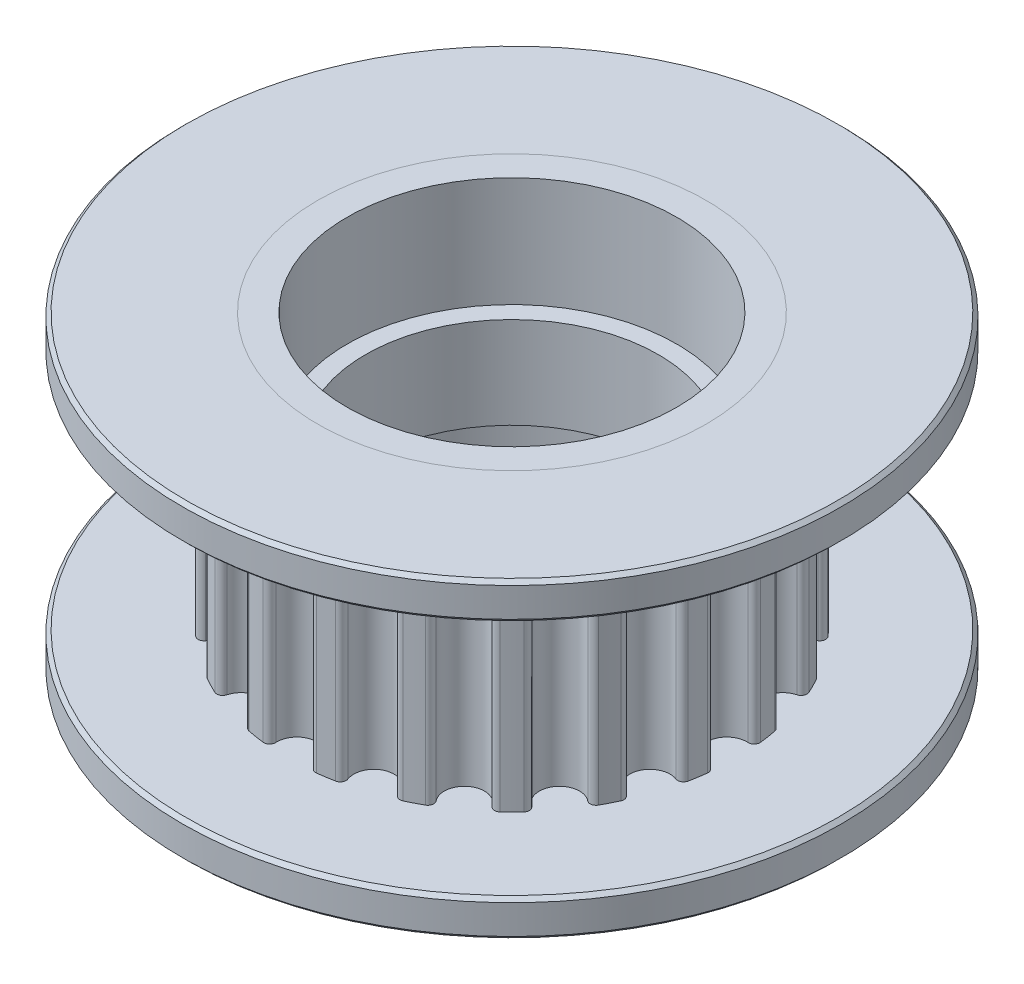
SolidWorks part; units mm, degrees
ref_plane "Přední rovina" through (0, 0, 0) normal (0, 0, 1) x (1, 0, 0)
ref_plane "Horní rovina" through (0, 0, 0) normal (0, 1, 0) x (1, 0, 0)
ref_plane "Pravá rovina" through (0, 0, 0) normal (1, 0, 0) x (0, 0, -1)
sketch "Skica1" plane through (0, 0, 0) normal (0, 0, 1) x (1, 0, 0)
  line L0 (0, 0) -> (0, 8.5) construction
  line L1 (4.5, 8.5) -> (5.3, 8.5)
  line L2 (5.3, 8.5) -> (5.3, 7.5)
  line L3 (5.3, 7.5) -> (9, 7.5)
  line L4 (9, 7.5) -> (9, 1)
  line L5 (4.5, 0) -> (5.3, 0)
  line L6 (5.3, 0) -> (5.3, 1)
  line L7 (5.3, 1) -> (9, 1)
  line L8 (4.5, 3) -> (4, 3)
  line L9 (4.5, 3) -> (4.5, 0)
  line L10 (4.5, 8.5) -> (4.5, 5.5)
  line L11 (4.5, 5.5) -> (4, 5.5)
  line L12 (4, 5.5) -> (4, 3)
  dimension "D1" = 6.5
  dimension "D2" = 2.5
  dimension "D3" = 3
  dimension "D4" = 9
  dimension "D5" = 4.5
  dimension "D6" = 5.3
  dimension "D7" = 8.5
revolve "Rotovat1" add sketch "Skica1" angle 360 about L0
sketch "Skica2" plane through (0, 7.5, 0) normal (0, 1, 0) x (1, 0, 0)
  arc A0 (-0.5492, 5.8991) -> (0.5492, 5.8991) centre (0, 5.87) ccw
  arc A1 (-0.5492, 5.8991) -> (-0.7281, 6.0665) centre (-0.709, 5.9076) ccw
  arc A2 (0.7281, 6.0665) -> (0.5492, 5.8991) centre (0.709, 5.9076) ccw
  arc A3 (1.1822, 5.9945) -> (0.7281, 6.0665) centre (0, 0) ccw
  arc A4 (1.3006, 5.7801) -> (2.3453, 5.4407) centre (1.8139, 5.5827) ccw
  arc A5 (1.3006, 5.7801) -> (1.1822, 5.9945) centre (1.1512, 5.8376) ccw
  arc A6 (2.5671, 5.5446) -> (2.3453, 5.4407) centre (2.4999, 5.3994) ccw
  arc A7 (2.9768, 5.3358) -> (2.5671, 5.5446) centre (0, 0) ccw
  arc A8 (3.0231, 5.0953) -> (3.9118, 4.4497) centre (3.4503, 4.7489) ccw
  arc A9 (3.0231, 5.0953) -> (2.9768, 5.3358) centre (2.8988, 5.1961) ccw
  arc A10 (4.1548, 4.4799) -> (3.9118, 4.4497) centre (4.046, 4.3626) ccw
  arc A11 (4.4799, 4.1548) -> (4.1548, 4.4799) centre (0, 0) ccw
  arc A12 (4.4497, 3.9118) -> (5.0953, 3.0231) centre (4.7489, 3.4503) ccw
  arc A13 (4.4497, 3.9118) -> (4.4799, 4.1548) centre (4.3626, 4.046) ccw
  arc A14 (5.3358, 2.9768) -> (5.0953, 3.0231) centre (5.1961, 2.8988) ccw
  arc A15 (5.5446, 2.5671) -> (5.3358, 2.9768) centre (0, 0) ccw
  arc A16 (5.4407, 2.3453) -> (5.7801, 1.3006) centre (5.5827, 1.8139) ccw
  arc A17 (5.4407, 2.3453) -> (5.5446, 2.5671) centre (5.3994, 2.4999) ccw
  arc A18 (5.9945, 1.1822) -> (5.7801, 1.3006) centre (5.8376, 1.1512) ccw
  arc A19 (6.0665, 0.7281) -> (5.9945, 1.1822) centre (0, 0) ccw
  arc A20 (5.8991, 0.5492) -> (5.8991, -0.5492) centre (5.87, 0) ccw
  arc A21 (5.8991, 0.5492) -> (6.0665, 0.7281) centre (5.9076, 0.709) ccw
  arc A22 (6.0665, -0.7281) -> (5.8991, -0.5492) centre (5.9076, -0.709) ccw
  arc A23 (5.9945, -1.1822) -> (6.0665, -0.7281) centre (0, 0) ccw
  arc A24 (5.7801, -1.3006) -> (5.4407, -2.3453) centre (5.5827, -1.8139) ccw
  arc A25 (5.7801, -1.3006) -> (5.9945, -1.1822) centre (5.8376, -1.1512) ccw
  arc A26 (5.5446, -2.5671) -> (5.4407, -2.3453) centre (5.3994, -2.4999) ccw
  arc A27 (5.3358, -2.9768) -> (5.5446, -2.5671) centre (0, 0) ccw
  arc A28 (5.0953, -3.0231) -> (4.4497, -3.9118) centre (4.7489, -3.4503) ccw
  arc A29 (5.0953, -3.0231) -> (5.3358, -2.9768) centre (5.1961, -2.8988) ccw
  arc A30 (4.4799, -4.1548) -> (4.4497, -3.9118) centre (4.3626, -4.046) ccw
  arc A31 (4.1548, -4.4799) -> (4.4799, -4.1548) centre (0, 0) ccw
  arc A32 (3.9118, -4.4497) -> (3.0231, -5.0953) centre (3.4503, -4.7489) ccw
  arc A33 (3.9118, -4.4497) -> (4.1548, -4.4799) centre (4.046, -4.3626) ccw
  arc A34 (2.9768, -5.3358) -> (3.0231, -5.0953) centre (2.8988, -5.1961) ccw
  arc A35 (2.5671, -5.5446) -> (2.9768, -5.3358) centre (0, 0) ccw
  arc A36 (2.3453, -5.4407) -> (1.3006, -5.7801) centre (1.8139, -5.5827) ccw
  arc A37 (2.3453, -5.4407) -> (2.5671, -5.5446) centre (2.4999, -5.3994) ccw
  arc A38 (1.1822, -5.9945) -> (1.3006, -5.7801) centre (1.1512, -5.8376) ccw
  arc A39 (0.7281, -6.0665) -> (1.1822, -5.9945) centre (0, 0) ccw
  arc A40 (0.5492, -5.8991) -> (-0.5492, -5.8991) centre (0, -5.87) ccw
  arc A41 (0.5492, -5.8991) -> (0.7281, -6.0665) centre (0.709, -5.9076) ccw
  arc A42 (-0.7281, -6.0665) -> (-0.5492, -5.8991) centre (-0.709, -5.9076) ccw
  arc A43 (-1.1822, -5.9945) -> (-0.7281, -6.0665) centre (0, 0) ccw
  arc A44 (-1.3006, -5.7801) -> (-2.3453, -5.4407) centre (-1.8139, -5.5827) ccw
  arc A45 (-1.3006, -5.7801) -> (-1.1822, -5.9945) centre (-1.1512, -5.8376) ccw
  arc A46 (-2.5671, -5.5446) -> (-2.3453, -5.4407) centre (-2.4999, -5.3994) ccw
  arc A47 (-2.9768, -5.3358) -> (-2.5671, -5.5446) centre (0, 0) ccw
  arc A48 (-3.0231, -5.0953) -> (-3.9118, -4.4497) centre (-3.4503, -4.7489) ccw
  arc A49 (-3.0231, -5.0953) -> (-2.9768, -5.3358) centre (-2.8988, -5.1961) ccw
  arc A50 (-4.1548, -4.4799) -> (-3.9118, -4.4497) centre (-4.046, -4.3626) ccw
  arc A51 (-4.4799, -4.1548) -> (-4.1548, -4.4799) centre (0, 0) ccw
  arc A52 (-4.4497, -3.9118) -> (-5.0953, -3.0231) centre (-4.7489, -3.4503) ccw
  arc A53 (-4.4497, -3.9118) -> (-4.4799, -4.1548) centre (-4.3626, -4.046) ccw
  arc A54 (-5.3358, -2.9768) -> (-5.0953, -3.0231) centre (-5.1961, -2.8988) ccw
  arc A55 (-5.5446, -2.5671) -> (-5.3358, -2.9768) centre (0, 0) ccw
  arc A56 (-5.4407, -2.3453) -> (-5.7801, -1.3006) centre (-5.5827, -1.8139) ccw
  arc A57 (-5.4407, -2.3453) -> (-5.5446, -2.5671) centre (-5.3994, -2.4999) ccw
  arc A58 (-5.9945, -1.1822) -> (-5.7801, -1.3006) centre (-5.8376, -1.1512) ccw
  arc A59 (-6.0665, -0.7281) -> (-5.9945, -1.1822) centre (0, 0) ccw
  arc A60 (-5.8991, -0.5492) -> (-5.8991, 0.5492) centre (-5.87, 0) ccw
  arc A61 (-5.8991, -0.5492) -> (-6.0665, -0.7281) centre (-5.9076, -0.709) ccw
  arc A62 (-6.0665, 0.7281) -> (-5.8991, 0.5492) centre (-5.9076, 0.709) ccw
  arc A63 (-5.9945, 1.1822) -> (-6.0665, 0.7281) centre (0, 0) ccw
  arc A64 (-5.7801, 1.3006) -> (-5.4407, 2.3453) centre (-5.5827, 1.8139) ccw
  arc A65 (-5.7801, 1.3006) -> (-5.9945, 1.1822) centre (-5.8376, 1.1512) ccw
  arc A66 (-5.5446, 2.5671) -> (-5.4407, 2.3453) centre (-5.3994, 2.4999) ccw
  arc A67 (-5.3358, 2.9768) -> (-5.5446, 2.5671) centre (0, 0) ccw
  arc A68 (-5.0953, 3.0231) -> (-4.4497, 3.9118) centre (-4.7489, 3.4503) ccw
  arc A69 (-5.0953, 3.0231) -> (-5.3358, 2.9768) centre (-5.1961, 2.8988) ccw
  arc A70 (-4.4799, 4.1548) -> (-4.4497, 3.9118) centre (-4.3626, 4.046) ccw
  arc A71 (-4.1548, 4.4799) -> (-4.4799, 4.1548) centre (0, 0) ccw
  arc A72 (-3.9118, 4.4497) -> (-3.0231, 5.0953) centre (-3.4503, 4.7489) ccw
  arc A73 (-3.9118, 4.4497) -> (-4.1548, 4.4799) centre (-4.046, 4.3626) ccw
  arc A74 (-2.9768, 5.3358) -> (-3.0231, 5.0953) centre (-2.8988, 5.1961) ccw
  arc A75 (-2.5671, 5.5446) -> (-2.9768, 5.3358) centre (0, 0) ccw
  arc A76 (-2.3453, 5.4407) -> (-1.3006, 5.7801) centre (-1.8139, 5.5827) ccw
  arc A77 (-2.3453, 5.4407) -> (-2.5671, 5.5446) centre (-2.4999, 5.3994) ccw
  arc A78 (-1.1822, 5.9945) -> (-1.3006, 5.7801) centre (-1.1512, 5.8376) ccw
  arc A79 (-0.7281, 6.0665) -> (-1.1822, 5.9945) centre (0, 0) ccw
  circle A81 centre (0, 0) radius 9
  point P3 (0, 0)
  point P143 (0, 0)
  point P144 (0, 0)
  dimension "D1" = 18
  dimension "D2" = 6.11
  dimension "D4" = 0.55
  dimension "D5" = 0.16
  dimension "D3" = 5.87
  dimension "D6" = 5.95
  dimension "D7" = 1.8365
  dimension "D8" = 0.4478
extrude "Odebrat vysunutím1" cut sketch "Skica2" against normal blind 6.5
sketch "Skica3" plane through (0, 7.5, 0) normal (0, 1, 0) x (1, 0, 0)
  circle A0 centre (0, 0) radius 9
  circle A1 centre (0, 0) radius 5.3
  dimension "D1" = 18
  dimension "D2" = 10.6
extrude "Přidat vysunutím1" add sketch "Skica3" along normal blind 1 separate body
sketch "Skica5" plane through (0, 1, 0) normal (0, -1, 0) x (1, 0, 0)
  circle A0 centre (0, 0) radius 9
  circle A1 centre (0, 0) radius 5.3
  dimension "D1" = 10.6
  dimension "D2" = 18
extrude "Přidat vysunutím2" add sketch "Skica5" along normal blind 1 separate body
chamfer "Zkosení1" distance 0.1 angle 45 2 edges at (-9, 7.5, 0) (-9, 8.5, 0)
chamfer "Zkosení2" distance 0.1 angle 45 2 edges at (9, 1, 0) (9, 0, 0)
